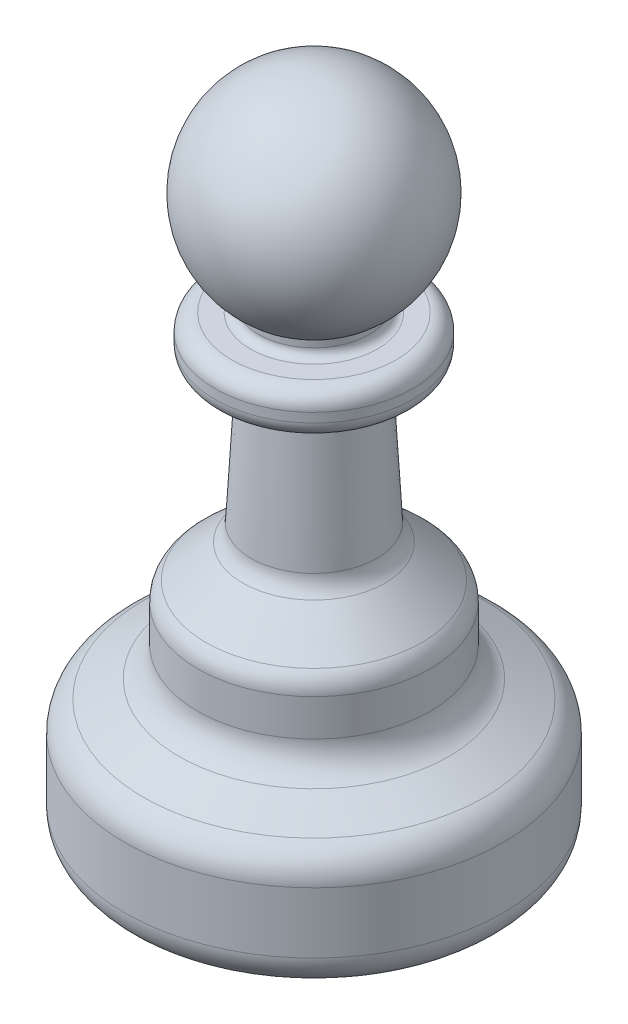
SolidWorks part; units mm, degrees
ref_plane "Front Plane" through (0, 0, 0) normal (0, 0, 1) x (1, 0, 0)
ref_plane "Top Plane" through (0, 0, 0) normal (0, 1, 0) x (1, 0, 0)
ref_plane "Right Plane" through (0, 0, 0) normal (1, 0, 0) x (0, 0, -1)
sketch "Sketch2" plane through (0, 0, 0) normal (0, 0, 1) x (1, 0, 0)
  line L0 (27.3333, 134) -> (136.6667, 134) construction
sketch "Sketch1" plane through (0, 0, 0) normal (0, 0, 1) x (1, 0, 0)
  line L0 (24.7471, 121.3211) -> (123.7354, 121.3211) construction
  line L1 (0, 0) -> (78.2676, 0) construction
  line L2 (25.4657, 80) -> (25.4657, 0) construction
  line L14 (2.7624, 4) -> (2.7624, 11.3086)
  line L15 (4.9975, 14.8982) -> (9.2734, 17.0006)
  line L16 (11.5085, 20.5902) -> (11.5085, 24.9958)
  line L17 (12.5061, 27.2297) -> (16.9367, 31.2012)
  line L18 (17.9297, 33.2714) -> (18.7846, 48.9179)
  line L19 (17.7861, 49.9725) -> (15.5901, 49.9725)
  line L20 (13.5901, 51.9725) -> (13.5901, 53.0861)
  line L21 (15.5901, 55.0861) -> (17.8422, 55.0861)
  line L22 (18.8422, 56.0861) -> (18.8422, 56.8991)
  line L23 (6.7624, 0) -> (25.4657, 0)
  line L24 (25.4657, 0) -> (25.4657, 80)
  arc A9 (25.4657, 80) -> (18.8422, 56.8991) centre (25.4657, 67.5) ccw
  arc A10 (15.5901, 55.0861) -> (13.5901, 53.0861) centre (15.5901, 53.0861) ccw
  arc A11 (15.5901, 49.9725) -> (13.5901, 51.9725) centre (15.5901, 51.9725) cw
  arc A12 (16.9367, 31.2012) -> (17.9297, 33.2714) centre (14.9342, 33.4351) ccw
  arc A13 (11.5085, 24.9958) -> (12.5061, 27.2297) centre (14.5085, 24.9958) cw
  arc A14 (11.5085, 20.5902) -> (9.2734, 17.0006) centre (7.5085, 20.5902) cw
  arc A15 (4.9975, 14.8982) -> (2.7624, 11.3086) centre (6.7624, 11.3086) ccw
  arc A16 (6.7624, 0) -> (2.7624, 4) centre (6.7624, 4) cw
  arc A17 (18.7846, 48.9179) -> (17.7861, 49.9725) centre (17.7861, 48.9725) ccw
  arc A18 (18.8422, 56.0861) -> (17.8422, 55.0861) centre (17.8422, 56.0861) cw
  point P32 (2.7624, 0)
  dimension "D8" = 4
  dimension "D9" = 4
  dimension "D10" = 1
  dimension "D11" = 1
  dimension "D1" = 25
  dimension "D2" = 2
  dimension "D4" = 2
  dimension "D5" = 3
  dimension "D6" = 3
  dimension "D7" = 4
  dimension "D3" = 80
revolve "Revolve1" add sketch "Sketch1" angle 360 about L24
